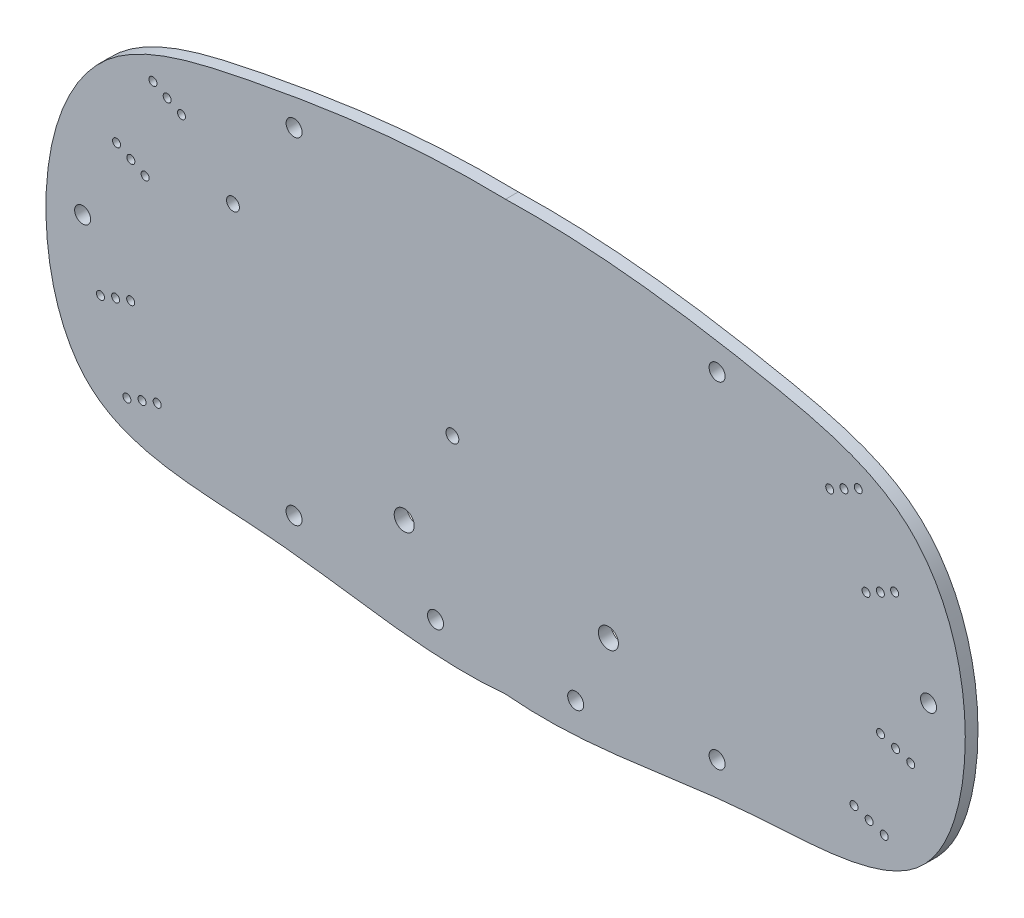
SolidWorks part; units mm, degrees
material "Acrylic (Medium-high impact)"
ref_plane "Front Plane" through (0, 0, 0) normal (0, 0, 1) x (1, 0, 0)
ref_plane "Top Plane" through (0, 0, 0) normal (0, 1, 0) x (1, 0, 0)
ref_plane "Right Plane" through (0, 0, 0) normal (1, 0, 0) x (0, 0, -1)
sketch "Sketch2" plane through (0, 0, 0) normal (0, 0, 1) x (1, 0, 0)
  circle A10 centre (105.6294, 50.8755) radius 2
  circle A11 centre (97.4088, 36.971) radius 1
  circle A12 centre (90.7902, 18.0979) radius 1
  circle A13 centre (90.0252, 67.0441) radius 1
  circle A14 centre (80.9467, 84.8649) radius 1
  circle A15 centre (52.8245, 12.2328) radius 2
  circle A16 centre (17.5, 7.3772) radius 2
  circle A24 centre (-17.5, 7.3772) radius 2
  circle A25 centre (-52.8245, 12.2328) radius 2
  circle A30 centre (-105.6294, 50.8755) radius 2
  circle A31 centre (93.6342, 38.2948) radius 1
  circle A32 centre (87.0156, 19.4217) radius 1
  circle A37 centre (84.5108, 86.6806) radius 1
  circle A38 centre (93.5894, 68.8598) radius 1
  circle A39 centre (88.075, 88.4963) radius 1
  circle A40 centre (97.1535, 70.6755) radius 1
  circle A41 centre (101.1834, 35.6473) radius 1
  circle A42 centre (94.5649, 16.7742) radius 1
  circle A43 centre (52.8245, 96.0993) radius 2
  circle A44 centre (-52.8245, 96.0993) radius 2
  circle A45 centre (-90.0252, 67.0441) radius 1
  circle A46 centre (-93.5894, 68.8598) radius 1
  circle A47 centre (-97.1535, 70.6755) radius 1
  circle A48 centre (-88.075, 88.4963) radius 1
  circle A49 centre (-84.5108, 86.6806) radius 1
  circle A50 centre (-80.9467, 84.8649) radius 1
  circle A51 centre (-101.1834, 35.6473) radius 1
  circle A52 centre (-97.4088, 36.971) radius 1
  circle A53 centre (-93.6342, 38.2948) radius 1
  circle A54 centre (-94.5649, 16.7742) radius 1
  circle A55 centre (-90.7902, 18.0979) radius 1
  circle A56 centre (-87.0156, 19.4217) radius 1
  spline S0 degree 3 poles (0, 0) (-20.953, -1.9173) (-52.0654, 6.5599) (-106.0768, 5.0272) (-118.9056, 49.2019) (-106.9965, 91.1309) (-54.7921, 103.3923) (-22.6856, 107.5733) (0, 107.0408) knots 0 0 0 0 0.21242 0.369252 0.478798 0.640374 0.766906 1 1 1 1
  spline S1 degree 3 poles (0, 0) (20.953, -1.9173) (52.0654, 6.5599) (106.0768, 5.0272) (118.9056, 49.2019) (106.9965, 91.1309) (54.7921, 103.3923) (22.6856, 107.5733) (0, 107.0408) knots 0 0 0 0 0.21242 0.369252 0.478798 0.640374 0.766906 1 1 1 1
  dimension "D1" = 4
  dimension "D2" = 2
  dimension "D3" = 2
  dimension "D4" = 2
  dimension "D5" = 2
  dimension "D8" = 4
  dimension "D9" = 4
  dimension "D14" = 2
  dimension "D15" = 2
  dimension "D13" = 4
  dimension "D6" = 20
  dimension "D7" = 20
  dimension "D10" = 17.5
  dimension "D11" = 4
  dimension "D12" = 4
extrude "Boss-Extrude1" add sketch "Sketch2" along normal blind 3.175
sketch "Sketch3" plane through (0, 0, 3.175) normal (0, 0, 1) x (1, 0, 0)
  circle A0 centre (25.6788, 24.9838) radius 2.5
  circle A1 centre (-25.3212, 24.9838) radius 2.5
  dimension "D1" = 5
extrude "Cut-Extrude1" cut sketch "Sketch3" against normal through all
sketch "Sketch6" plane through (0, 0, 3.175) normal (0, 0, 1) x (1, 0, 0)
  circle A0 centre (-13.2868, 49.2077) radius 1.6
  circle A1 centre (-68.0868, 72.0077) radius 1.6
  dimension "D1" = 3.2
  dimension "D2" = 3.2
  dimension "D3" = 22.8
  dimension "D4" = 54.8
extrude "Cut-Extrude3" cut sketch "Sketch6" against normal through all
